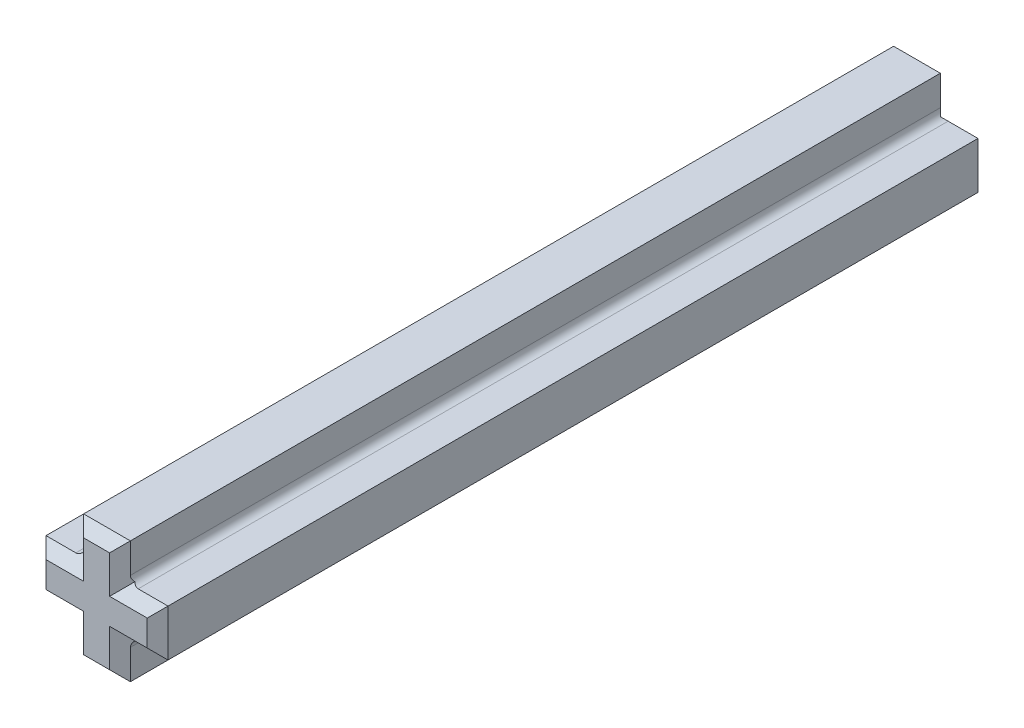
SolidWorks part; units mm, degrees
ref_plane "Front Plane" through (0, 0, 0) normal (0, 0, 1) x (1, 0, 0)
ref_plane "Top Plane" through (0, 0, 0) normal (0, 1, 0) x (1, 0, 0)
ref_plane "Right Plane" through (0, 0, 0) normal (1, 0, 0) x (0, 0, -1)
sketch "Sketch1" plane through (0, 0, 0) normal (0, 0, 1) x (1, 0, 0)
  line L0 (0.9, -0.9) -> (0.9, -2.35)
  line L1 (-2.35, 0.9) -> (-0.9, 0.9)
  line L2 (-2.35, 0.9) -> (-2.35, -0.9)
  line L3 (-2.35, -0.9) -> (-0.9, -0.9)
  line L4 (2.35, 0.9) -> (2.35, -0.9)
  line L5 (-2.35, 0.9) -> (2.35, -0.9) construction
  line L6 (-2.35, -0.9) -> (2.35, 0.9) construction
  line L7 (-0.9, 2.35) -> (0.9, 2.35)
  line L8 (-0.9, 2.35) -> (-0.9, 0.9)
  line L9 (-0.9, -2.35) -> (0.9, -2.35)
  line L10 (0.9, 2.35) -> (0.9, 0.9)
  line L11 (-0.9, 2.35) -> (0.9, -2.35) construction
  line L12 (-0.9, -2.35) -> (0.9, 2.35) construction
  line L13 (-0.9, -0.9) -> (-0.9, -2.35)
  line L14 (0.9, -0.9) -> (2.35, -0.9)
  line L15 (0.9, 0.9) -> (2.35, 0.9)
  circle A0 centre (0, 0) radius 2.35 construction
  dimension "D1" = 4.7
  dimension "D2" = 1.8
  dimension "D3" = 1.8
  dimension "D4" = 4.7
  dimension "D5" = 4.7
extrude "Boss-Extrude1" add sketch "Sketch1" along normal mid plane 32
chamfer "Chamfer1" distance 0.4 angle 45 24 edges at (2.35, 0, -16) (1.625, 0.9, -16) (0.9, 1.625, -16) (0, 2.35, -16) (-0.9, 1.625, -16) (-1.625, 0.9, -16) (-2.35, 0, -16) (-1.625, -0.9, -16) (-0.9, -1.625, -16) (0, -2.35, -16) (0.9, -1.625, -16) (1.625, -0.9, -16) (0.9, -1.625, 16) (0, -2.35, 16) (-0.9, -1.625, 16) (-1.625, -0.9, 16) (-2.35, 0, 16) (-1.625, 0.9, 16) (-0.9, 1.625, 16) (0, 2.35, 16) (0.9, 1.625, 16) (1.625, 0.9, 16) (2.35, 0, 16) (1.625, -0.9, 16)
fillet "Fillet1" radius 0.3 4 edges at (-0.9, -0.9, 0) (-0.9, 0.9, 0) (0.9, -0.9, 0) (0.9, 0.9, 0)
